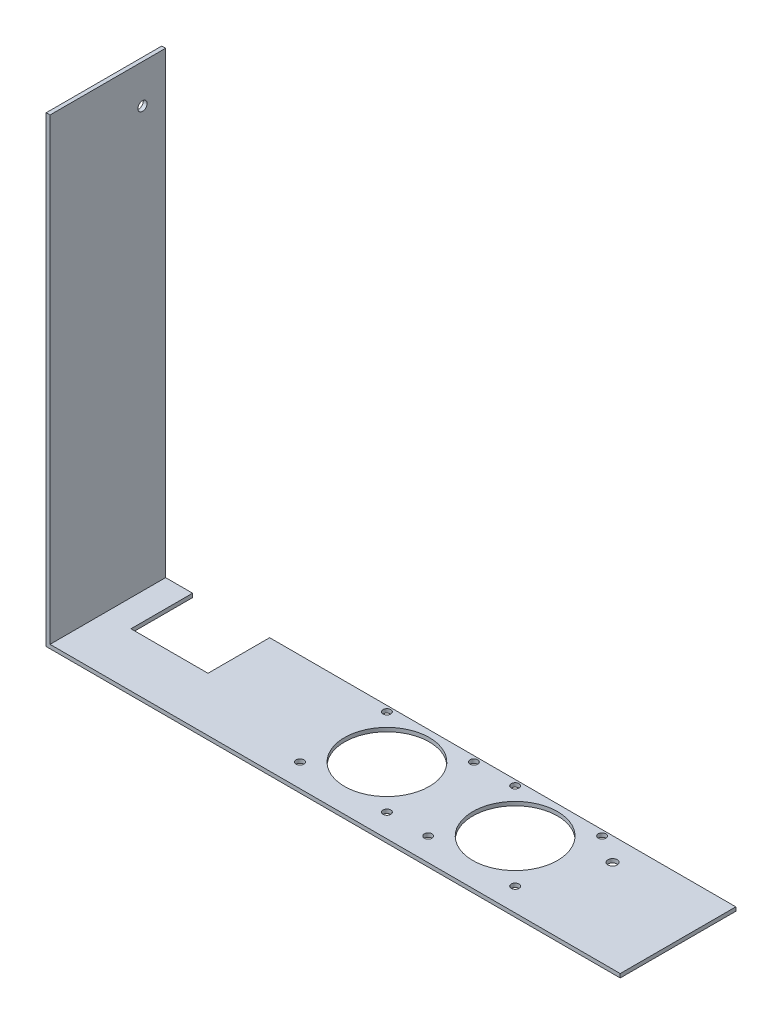
SolidWorks part; units mm, degrees
ref_plane "Front Plane" through (0, 0, 0) normal (0, 0, 1) x (1, 0, 0)
ref_plane "Top Plane" through (0, 0, 0) normal (0, 1, 0) x (1, 0, 0)
ref_plane "Right Plane" through (0, 0, 0) normal (1, 0, 0) x (0, 0, -1)
sketch "Sketch1" plane through (0, 0, 0) normal (0, 0, 1) x (1, 0, 0)
  line L0 (0, 0) -> (0, 381)
  line L5 (0, 381) -> (3.175, 381)
  line L6 (3.175, 381) -> (3.175, 3.175)
  line L7 (3.175, 3.175) -> (473.075, 3.175)
  line L8 (473.075, 3.175) -> (473.075, 0)
  line L9 (473.075, 0) -> (0, 0)
  dimension "D1" = 3.175
  dimension "D2" = 3.175
  dimension "D3" = 381
  dimension "D4" = 473.075
extrude "Boss-Extrude1" add sketch "Sketch1" along normal blind 95.25
sketch "Sketch2" plane through (0, 3.175, 0) normal (0, 1, 0) x (1, 0, 0)
  line L1 (473.075, -95.25) -> (3.175, -95.25) construction
  circle A0 centre (190.119, -4.572) radius 3.175
  circle A1 centre (190.119, -76.2) radius 3.175
  circle A2 centre (261.747, -4.572) radius 3.175
  circle A3 centre (261.747, -76.2) radius 3.175
  circle A4 centre (295.783, -76.2) radius 3.175
  circle A5 centre (295.783, -4.572) radius 3.175
  circle A6 centre (367.411, -76.2) radius 3.175
  circle A7 centre (367.411, -4.572) radius 3.175
  dimension "D3" = 6.35
  dimension "D1" = 6.35
  dimension "D2" = 19.05
  dimension "D4" = 71.628
  dimension "D5" = 71.628
  dimension "D6" = 71.628
  dimension "D7" = 6.35
  dimension "D8" = 6.35
extrude "Cut-Extrude1" cut sketch "Sketch2" against normal blind 152.4
sketch "Sketch4" plane through (0, 0, 0) normal (0, -1, 0) x (1, 0, 0)
  line L0 (473.075, 95.25) -> (473.075, 0) construction
  line L1 (0, 0) -> (473.075, 0) construction
  circle A0 centre (225.933, 40.386) radius 34.925
  circle A1 centre (331.597, 40.386) radius 34.925
  circle A2 centre (390.525, 19.05) radius 3.81
  dimension "D1" = 69.85
  dimension "D2" = 82.55
  dimension "D3" = 19.05
extrude "Cut-Extrude2" cut sketch "Sketch4" against normal blind 381
sketch "Sketch5" plane through (0, 0, 0) normal (-1, 0, 0) x (0, 0, 1)
  line L0 (95.25, 381) -> (0, 381) construction
  line L1 (0, 381) -> (0, 0) construction
  circle A0 centre (19.05, 349.25) radius 3.81
  dimension "D1" = 31.75
  dimension "D2" = 19.05
extrude "Cut-Extrude3" cut sketch "Sketch5" against normal blind 12.7
sketch "Sketch6" plane through (0, 0, 0) normal (0, -1, 0) x (1, 0, 0)
  line L1 (0, 0) -> (473.075, 0) construction
  line L3 (25.4, 0) -> (88.9, 0)
  line L4 (25.4, 0) -> (25.4, 50.8)
  line L5 (25.4, 50.8) -> (88.9, 50.8)
  line L6 (88.9, 0) -> (88.9, 50.8)
extrude "Cut-Extrude4" cut sketch "Sketch6" against normal blind 76.708
